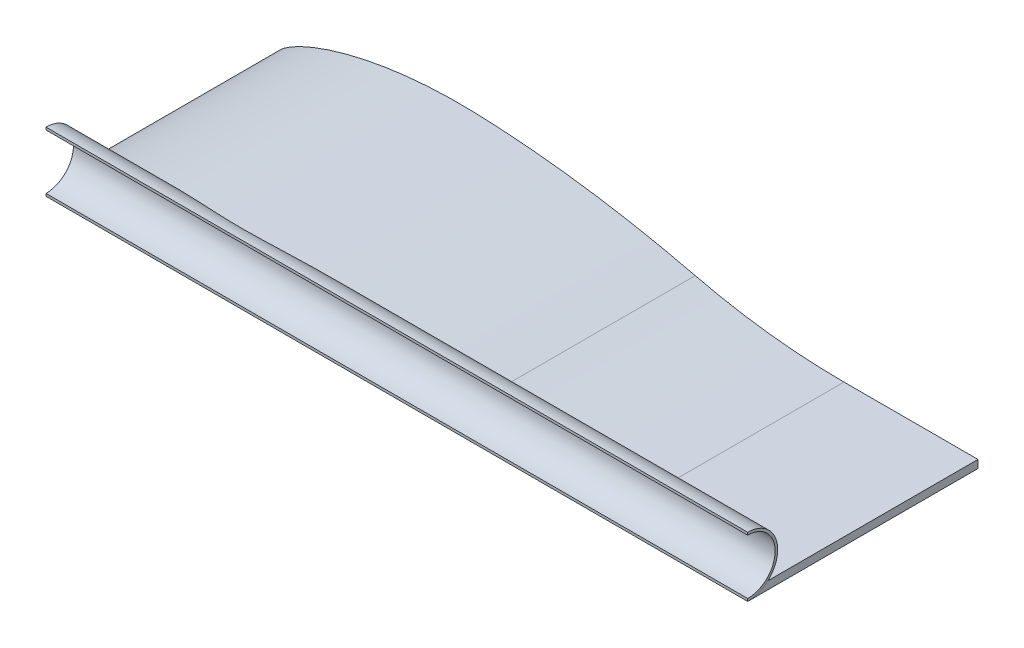
SolidWorks part; units mm, degrees
ref_plane "Front Plane" through (0, 0, 0) normal (0, 0, 1) x (1, 0, 0)
ref_plane "Top Plane" through (0, 0, 0) normal (0, 1, 0) x (1, 0, 0)
ref_plane "Right Plane" through (0, 0, 0) normal (1, 0, 0) x (0, 0, -1)
curve "Curve1"
  spline degree 3 poles (302.9843, 0.2066, 0) (305.2463, -0.0888, 0) (303.0423, 0.5058, 0) (301.2607, 1.1313, 0) (296.8595, 2.4314, 0) (291.4283, 4.0595, 0) (284.2715, 6.1062, 0) (275.7591, 8.441, 0) (265.8676, 11.0139, 0) (254.7283, 13.724, 0) (242.4522, 16.5013, 0) (229.1619, 19.2495, 0) (215.0022, 21.8919, 0) (200.1221, 24.3477, 0) (184.6818, 26.5449, 0) (168.8517, 28.4234, 0) (152.8082, 29.9307, 0) (136.7266, 31.0049, 0) (120.7051, 31.6889, 0) (104.9137, 31.6962, 0) (89.5649, 30.8862, 0) (74.9378, 29.3709, 0) (61.2207, 27.2233, 0) (48.5868, 24.554, 0) (37.1861, 21.5011, 0) (27.1553, 18.1971, 0) (18.5969, 14.8045, 0) (11.6064, 11.436, 0) (6.2054, 8.2632, 0) (2.4621, 5.3102, 0) (0.1728, 2.7181, 0) (-0.3667, -0.1067, 0) (1.6185, -2.1752, 0) (4.9031, -3.1118, 0) (9.5405, -3.659, 0) (15.6223, -3.6847, 0) (23.0877, -3.3095, 0) (31.8617, -2.5607, 0) (41.8437, -1.5362, 0) (52.932, -0.3245, 0) (65.0085, 0.9827, 0) (77.9641, 2.2775, 0) (91.674, 3.4466, 0) (106.0204, 4.4121, 0) (120.9553, 5.0518, 0) (136.3391, 5.4103, 0) (152.0077, 5.7293, 0) (167.7158, 5.8914, 0) (183.2867, 5.9078, 0) (198.553, 5.7595, 0) (213.3478, 5.4574, 0) (227.5084, 5.0134, 0) (240.8771, 4.4585, 0) (253.3023, 3.8196, 0) (264.6365, 3.1406, 0) (274.7593, 2.4517, 0) (283.5118, 1.8033, 0) (290.9024, 1.2074, 0) (296.5367, 0.7424, 0) (301.0977, 0.3102, 0) (302.9843, 0.2066, 0) (305.2463, -0.0888, 0) (303.0423, 0.5058, 0) knots -0.012269 -0.005489 -0.001366 0 0.001375 0.005484 0.012273 0.021682 0.033581 0.047831 0.064306 0.082777 0.103064 0.124929 0.148149 0.172445 0.197572 0.223269 0.249228 0.275186 0.300901 0.326463 0.351222 0.374906 0.39727 0.418072 0.43708 0.454093 0.46892 0.481392 0.491447 0.499024 0.504294 0.507922 0.51154 0.516781 0.524216 0.533992 0.546034 0.56022 0.576403 0.594371 0.613951 0.634917 0.657089 0.68023 0.704175 0.72909 0.754354 0.779668 0.80476 0.829359 0.853209 0.876041 0.897604 0.917662 0.93597 0.95231 0.966503 0.97835 0.987731 0.994511 0.998634 1 1.001375 1.005484 1.012273 periodic
sketch "Sketch1" plane through (0, 0, 0) normal (0, 0, 1) x (1, 0, 0)
  line L0 (397.4027, 0) -> (397.4027, -11.2558) construction
  line L1 (397.4027, -11.2558) -> (0, -11.2558) construction
  line L2 (0, -11.2558) -> (0, 0) construction
  line L3 (397.4027, 0) -> (397.4027, 42.136) construction
  line L4 (397.4027, 42.136) -> (0, 42.136) construction
  line L5 (0, 42.136) -> (0, 0) construction
  line L6 (16.8245, -3.584) -> (563.88, -3.584)
  line L7 (563.88, -3.584) -> (563.88, 2.766)
  line L8 (563.88, 2.766) -> (388.5279, 2.766)
  line L9 (397.4027, 0) -> (0, 0) construction
  spline S1 degree 3 poles (395.0322, 0.2772) (397.9852, -0.1177) (395.1091, 0.6677) (392.7847, 1.492) (387.0417, 3.208) (379.9549, 5.3566) (370.6158, 8.059) (359.5074, 11.1431) (346.5989, 14.5439) (332.0611, 18.1288) (316.0389, 21.8064) (298.6919, 25.4499) (280.2091, 28.9588) (260.7844, 32.227) (240.6272, 35.1598) (219.9595, 37.6778) (199.0115, 39.7119) (178.012, 41.1805) (157.0894, 42.1393) (136.4647, 42.2132) (116.4146, 41.2179) (97.3043, 39.2985) (79.38, 36.5495) (62.8681, 33.1148) (47.9656, 29.1739) (34.851, 24.8995) (23.6593, 20.5034) (14.5153, 16.1325) (7.4482, 12.0105) (2.5471, 8.169) (-0.4534, 4.7928) (-1.1696, 1.1056) (1.4149, -1.6041) (5.701, -2.8408) (11.7555, -3.5745) (19.6988, -3.6327) (29.4507, -3.1732) (40.9133, -2.231) (53.9547, -0.9336) (68.4418, 0.6036) (84.2201, 2.2618) (101.1464, 3.9) (119.0574, 5.371) (137.7989, 6.5735) (157.3077, 7.348) (177.4016, 7.7535) (197.8673, 8.1063) (218.3839, 8.2538) (238.7209, 8.2118) (258.6593, 7.9558) (277.9812, 7.5009) (296.4742, 6.8632) (313.9325, 6.084) (330.1583, 5.1987) (344.9588, 4.2658) (358.1772, 3.3246) (369.606, 2.4422) (379.2564, 1.6336) (386.6132, 1.0034) (392.5685, 0.4203) (395.0322, 0.2772) (397.9852, -0.1177) (395.1091, 0.6677) knots -0.012269 -0.005489 -0.001366 0 0.001375 0.005484 0.012273 0.021682 0.033581 0.047831 0.064306 0.082777 0.103064 0.124929 0.148149 0.172445 0.197572 0.223269 0.249228 0.275186 0.300901 0.326463 0.351222 0.374906 0.39727 0.418072 0.43708 0.454093 0.46892 0.481392 0.491447 0.499024 0.504294 0.507922 0.51154 0.516781 0.524216 0.533992 0.546034 0.56022 0.576403 0.594371 0.613951 0.634917 0.657089 0.68023 0.704175 0.72909 0.754354 0.779668 0.80476 0.829359 0.853209 0.876041 0.897604 0.917662 0.93597 0.95231 0.966503 0.97835 0.987731 0.994511 0.998634 1 1.001375 1.005484 1.012273 only from (397.4027, 0) to (397.4027, 0)
  dimension "D1" = 45.72
  dimension "D2" = 563.88
  dimension "D3" = 6.35
  dimension "D4" = 397.4027
extrude "Boss-Extrude1" add sketch "Sketch1" along normal blind 185.42 contours S1 L6 L7 L8 | S1
fillet "Fillet1" radius 508 1 edges at (388.5279, 2.766, 92.71)
sketch "Sketch2" plane through (563.88, 0, 0) normal (1, 0, 0) x (0, 0, -1)
  line L0 (-185.42, -3.584) -> (-185.42, 44.676)
  arc A0 (-185.42, 44.676) -> (-185.42, -3.584) centre (-185.42, 20.546) cw
  line M3 (0, 2.766) -> (-185.42, 2.766)
  line M4 (-185.42, 2.766) -> (-185.42, -3.584)
  dimension "D1" = 48.26
extrude "Boss-Extrude2" add sketch "Sketch2" along normal through all and the other way through all contours A0 L0 M3 | A0 M3 M4
sketch "Sketch3" plane through (563.88, 0, 0) normal (1, 0, 0) x (0, 0, -1)
  line L0 (-185.42, -3.584) -> (-185.42, 44.676) construction
  line L1 (-185.42, 42.644) -> (-185.42, -1.552)
  arc A0 (-185.42, 42.644) -> (-185.42, -1.552) centre (-185.42, 20.546) cw
  arc A1 (-185.42, -3.584) -> (-185.42, 44.676) centre (-185.42, 20.546) ccw construction
  dimension "D1" = 2.032
extrude "Cut-Extrude1" cut sketch "Sketch3" against normal through all and the other way through all
